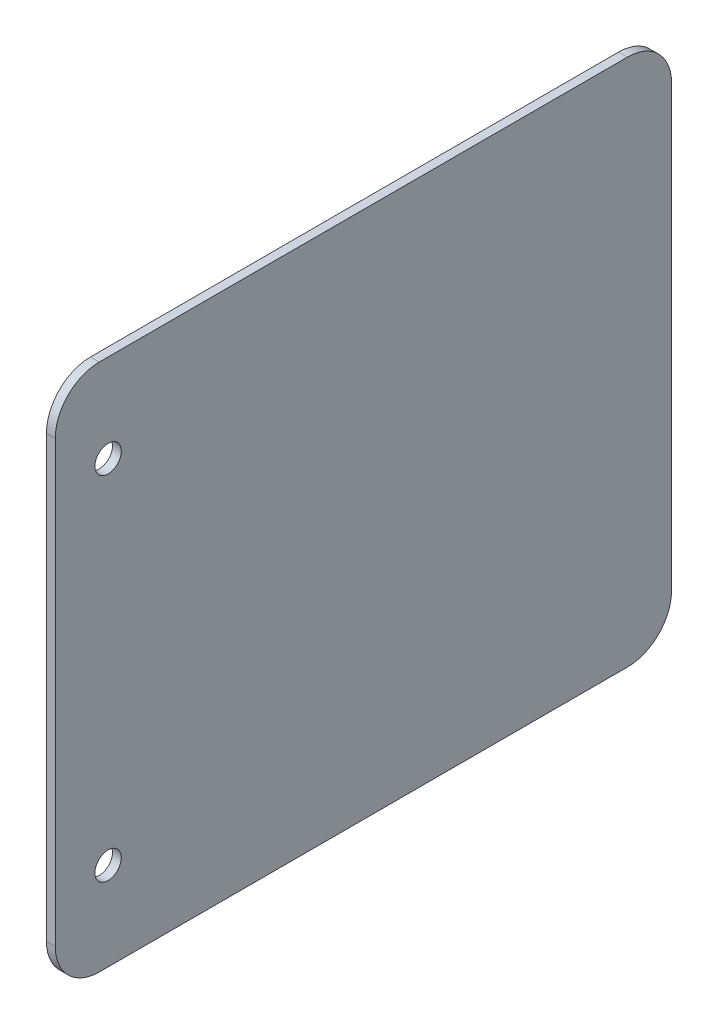
SolidWorks part; units mm, degrees
ref_plane "Front Plane" through (0, 0, 0) normal (0, 0, 1) x (1, 0, 0)
ref_plane "Top Plane" through (0, 0, 0) normal (0, 1, 0) x (1, 0, 0)
ref_plane "Right Plane" through (0, 0, 0) normal (1, 0, 0) x (0, 0, -1)
sketch "Sketch1" plane through (0, 0, 0) normal (1, 0, 0) x (0, 0, -1)
  line L0 (55, 0) -> (-55, 0) construction
  line L1 (-30, 30) -> (30, 30)
  line L2 (-35, 25) -> (-35, -25)
  line L3 (-30, -30) -> (30, -30)
  line L4 (35, 25) -> (35, -25)
  line L5 (0, 55) -> (0, -55) construction
  arc A0 (-35, -25) -> (-30, -30) centre (-30, -25) ccw
  arc A1 (30, -30) -> (35, -25) centre (30, -25) ccw
  arc A2 (35, 25) -> (30, 30) centre (30, 25) ccw
  arc A3 (-30, 30) -> (-35, 25) centre (-30, 25) ccw
  dimension "D1" = 5
  dimension "D2" = 70
  dimension "D3" = 60
  dimension "D4" = 30
  dimension "D5" = 35
extrude "Boss-Extrude1" add sketch "Sketch1" against normal blind 1
sketch "Sketch2" plane through (0, 0, 0) normal (1, 0, 0) x (0, 0, -1)
  line L0 (-29, 23.0144) -> (-29, -23.9463) construction
  line L1 (0.55, 0) -> (-0.55, 0) construction
  line L3 (-35, 25) -> (-35, -25) construction
  circle A0 centre (-29, 20) radius 1.5
  circle A1 centre (-29, -20) radius 1.5
  dimension "D1" = 3
  dimension "D2" = 3
  dimension "D3" = 40
  dimension "D4" = 20
  dimension "D5" = 6
extrude "Cut-Extrude1" cut sketch "Sketch2" against normal blind 10
